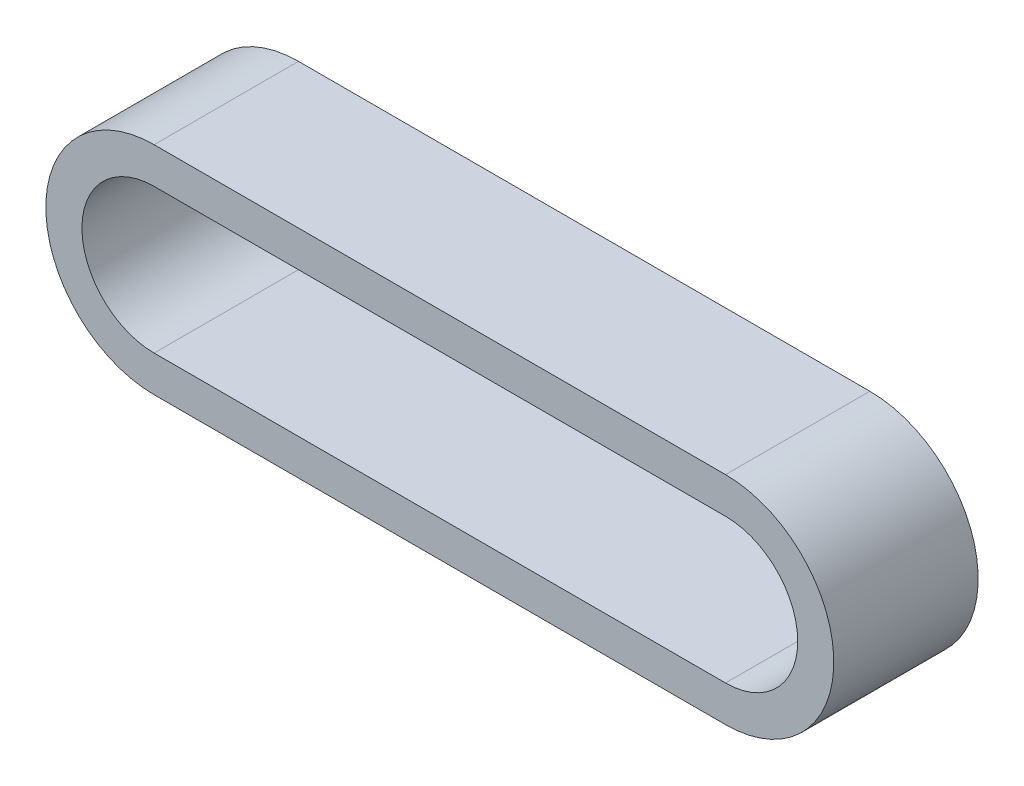
SolidWorks part; units mm, degrees
material "天然橡胶"
ref_plane "前视基准面" through (0, 0, 0) normal (0, 0, 1) x (1, 0, 0)
ref_plane "上视基准面" through (0, 0, 0) normal (0, 1, 0) x (1, 0, 0)
ref_plane "右视基准面" through (0, 0, 0) normal (1, 0, 0) x (0, 0, -1)
sketch "草图1" plane through (0, 0, 0) normal (0, 0, 1) x (1, 0, 0)
  line L0 (0, 0) -> (23.75, 0) construction
  line L1 (0, 3) -> (23.75, 3)
  line L2 (0, -3) -> (23.75, -3)
  line L3 (0, 0) -> (23.75, 0) construction
  line L4 (0, 4.5) -> (23.75, 4.5)
  line L5 (0, -4.5) -> (23.75, -4.5)
  arc A0 (0, 3) -> (0, -3) centre (0, 0) ccw
  arc A1 (23.75, -3) -> (23.75, 3) centre (23.75, 0) ccw
  arc A2 (0, 4.5) -> (0, -4.5) centre (0, 0) ccw
  arc A3 (23.75, -4.5) -> (23.75, 4.5) centre (23.75, 0) ccw
  point P3 (11.875, 0)
  point P10 (11.875, 0)
  dimension "D2" = 3
  dimension "D3" = 4.5
  dimension "D1" = 23.75
extrude "凸台-拉伸1" add sketch "草图1" along normal blind 6
